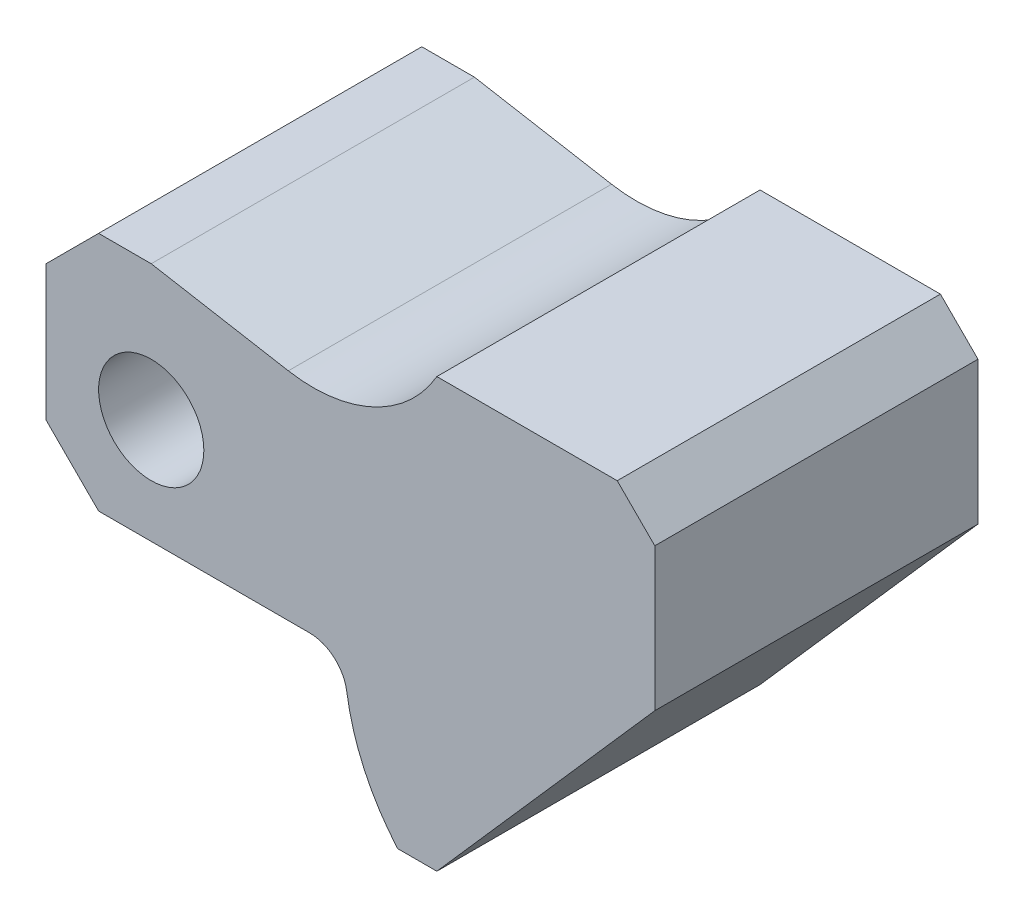
SolidWorks part; units mm, degrees
material "AISI 1020"
ref_plane "Plan de face" through (0, 0, 0) normal (0, 0, 1) x (1, 0, 0)
ref_plane "Plan de dessus" through (0, 0, 0) normal (0, 1, 0) x (1, 0, 0)
ref_plane "Plan de droite" through (0, 0, 0) normal (1, 0, 0) x (0, 0, -1)
sketch "Esquisse1" plane through (0, 0, 0) normal (0, 0, 1) x (1, 0, 0)
  line L0 (35.0103, -5.2308) -> (59.0103, -5.2308)
  line L1 (59.0103, -5.2308) -> (64.0103, -10.2308)
  line L2 (64.0103, -10.2308) -> (64.0103, -29.2308)
  line L3 (64.0103, -29.2308) -> (35.0103, -62.2308)
  line L4 (35.0103, -62.2308) -> (29.7984, -62.2308)
  line L6 (18.0769, -43.2308) -> (-9.9897, -43.2308)
  line L7 (-9.9897, -43.2308) -> (-16.9897, -36.2308)
  line L8 (-16.9897, -36.2308) -> (-16.9897, -18.2308)
  line L9 (-16.9897, -18.2308) -> (-9.9897, -11.2308)
  line L12 (-9.9897, -11.2308) -> (-2.9897, -11.2308)
  line L18 (-2.9897, -11.2308) -> (15.2534, -14.4476)
  arc A1 (23.0226, -47.4955) -> (18.0769, -43.2308) centre (18.0769, -48.2308) ccw
  arc A2 (35.0103, -5.2308) -> (15.2534, -14.4476) centre (18.5527, 4.2638) cw
  arc A3 (29.7984, -62.2308) -> (23.0226, -47.4955) centre (51.7073, -43.2308) cw
  circle A4 centre (-2.9897, -29.2308) radius 7
  point P17 (24.1901, -43.2308)
  dimension "D15" = 5
  dimension "D17" = 29
  dimension "D1" = 29
  dimension "D2" = 24
  dimension "D3" = 57
  dimension "D4" = 5
  dimension "D5" = 7
  dimension "D6" = 32
  dimension "D7" = 7
  dimension "D8" = 19
  dimension "D10" = 135
  dimension "D11" = 81
  dimension "D13" = 135
  dimension "D12" = 14
  dimension "D14" = 29
  dimension "D16" = 190
  dimension "D18" = 14
  dimension "D19" = 14
  dimension "D20" = 135
  dimension "D9" = 19
  dimension "D21" = 19
extrude "Boss.-Extru.2" add sketch "Esquisse1" along normal blind 43
equation "\"A\"= 81"
equation "\"B\"= 57"
equation "\"C\"= 43"
equation "\"D11@Esquisse1\"=\"A\""
equation "\"D3@Esquisse1\"=\"B\""
equation "\"D1@Boss.-Extru.2\"=\"C\""
